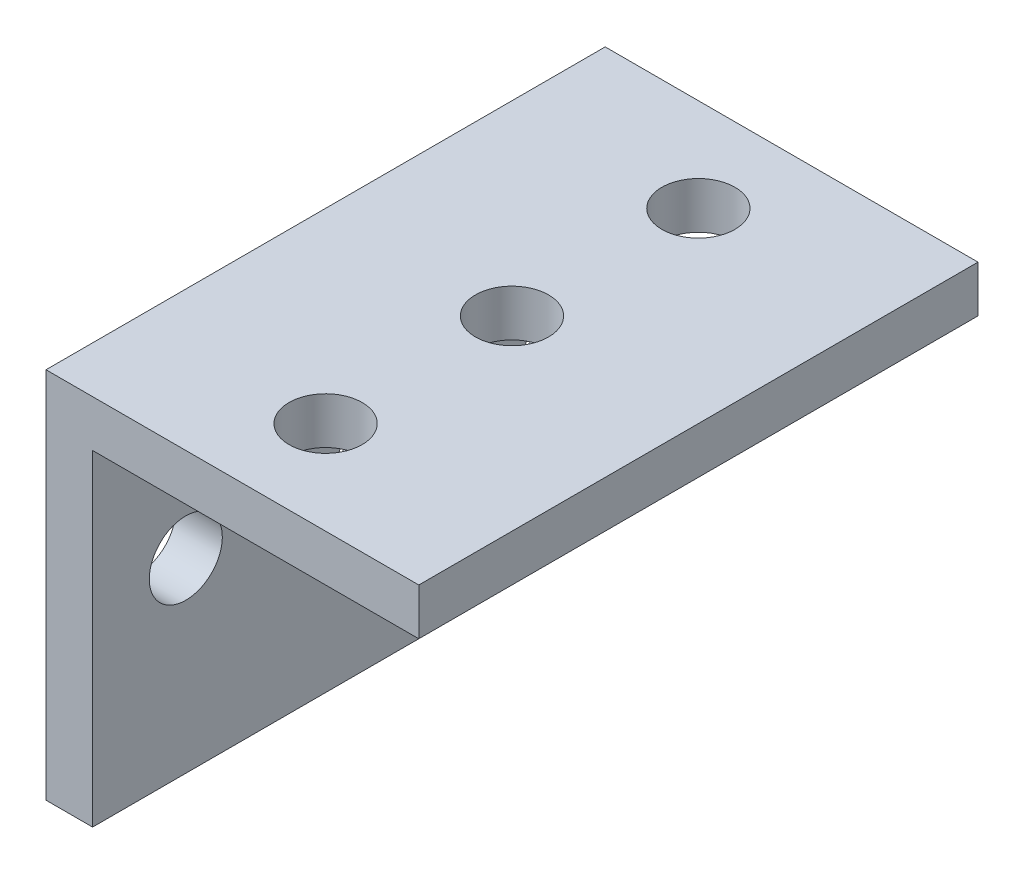
SolidWorks part; units mm, degrees
ref_plane "Front Plane" through (0, 0, 0) normal (0, 0, 1) x (1, 0, 0)
ref_plane "Top Plane" through (0, 0, 0) normal (0, 1, 0) x (1, 0, 0)
ref_plane "Right Plane" through (0, 0, 0) normal (1, 0, 0) x (0, 0, -1)
sketch "Sketch2" plane through (0, 0, 0) normal (0, 0, 1) x (1, 0, 0)
  line L0 (0, 0) -> (0, -25.4)
  line L1 (0, -25.4) -> (3.175, -25.4)
  line L2 (3.175, -25.4) -> (3.175, -3.175)
  line L3 (3.175, -3.175) -> (25.4, -3.175)
  line L4 (25.4, -3.175) -> (25.4, 0)
  line L5 (25.4, 0) -> (0, 0)
  dimension "D1" = 3.175
  dimension "D2" = 25.4
  dimension "D3" = 25.4
extrude "Boss-Extrude1" add sketch "Sketch2" along normal blind 38.1
sketch "Sketch5" plane through (3.175, 0, 0) normal (1, 0, 0) x (0, 0, -1)
  line L0 (-38.1, -25.4) -> (0, -25.4) construction
  line L1 (0, -25.4) -> (0, -3.175) construction
  circle A1 centre (-6.35, -12.7) radius 2.4892
  circle A2 centre (-19.05, -12.7) radius 2.4892
  circle A3 centre (-31.75, -12.7) radius 2.4892
  circle A4 centre (-44.45, -12.7) radius 2.4892
  dimension "D1" = 4.9784
  dimension "D2" = 12.7
  dimension "D3" = 6.35
  dimension "D4" = 4
  dimension "D5" = 12.7
extrude "Cut-Extrude1" cut sketch "Sketch5" against normal through all
sketch "Sketch6" plane through (0, -3.175, 0) normal (0, -1, 0) x (1, 0, 0)
  line L0 (3.175, 0) -> (25.4, 0) construction
  line L1 (25.4, 38.1) -> (25.4, 0) construction
  circle A0 centre (12.7, 6.35) radius 2.4892
  circle A1 centre (12.7, 19.05) radius 2.4892
  circle A2 centre (12.7, 31.75) radius 2.4892
  circle A3 centre (12.7, 44.45) radius 2.4892
  dimension "D3" = 4.9784
  dimension "D1" = 6.35
  dimension "D2" = 12.7
  dimension "D5" = 12.7
  dimension "D4" = 4
extrude "Cut-Extrude2" cut sketch "Sketch6" against normal through all
